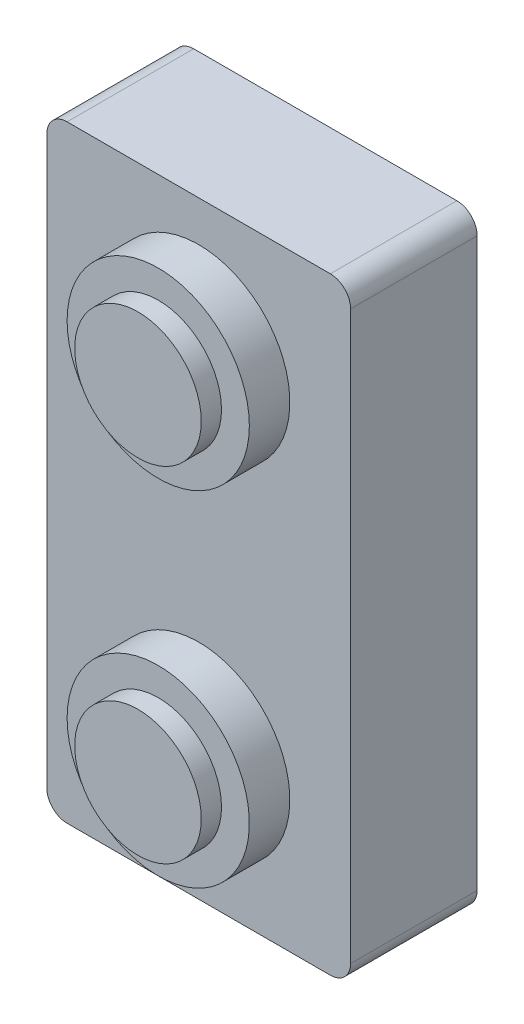
SolidWorks part; units mm, degrees
ref_plane "前视基准面" through (0, 0, 0) normal (0, 0, 1) x (1, 0, 0)
ref_plane "上视基准面" through (0, 0, 0) normal (0, 1, 0) x (1, 0, 0)
ref_plane "右视基准面" through (0, 0, 0) normal (1, 0, 0) x (0, 0, -1)
sketch "草图1" plane through (0, 0, 0) normal (0, 0, 1) x (1, 0, 0)
  line L0 (0, 0) -> (50000, 0) construction
  line L1 (0, 0) -> (0, -50000) construction
  line L3 (15, 30) -> (-15, 30)
  line L4 (15, 30) -> (15, -30)
  line L5 (15, -30) -> (-15, -30)
  line L6 (-15, 30) -> (-15, -30)
extrude "凸台-拉伸1" add sketch "草图1" along normal blind 12.5
sketch "草图2" plane through (0, 0, 12.5) normal (0, 0, 1) x (1, 0, 0)
  line L0 (0, 0) -> (0, 50000) construction
  line L1 (0, 0) -> (50000, 0) construction
  line L2 (-15, 30) -> (35340.3391, -35325.3391) construction
  line L3 (15, -30) -> (15, 30) construction
  line L4 (15, 30) -> (-35340.3391, -35325.3391) construction
  line L5 (-15, 30) -> (-15, -30) construction
  line L6 (-15, 0) -> (35340.3391, -35355.3391) construction
  line L7 (15, 0) -> (-35340.3391, -35355.3391) construction
  circle A2 centre (0, 17) radius 9
  circle A3 centre (0, -17) radius 9
  point P10 (15, 0)
  point P16 (-15, 0)
  dimension "D1" = 34
extrude "凸台-拉伸2" add sketch "草图2" along normal blind 4
sketch "草图3" plane through (0, 0, 16.5) normal (0, 0, 1) x (1, 0, 0)
  circle A0 centre (0, 17) radius 6.25
  circle A1 centre (0, -17) radius 6.25
extrude "凸台-拉伸3" add sketch "草图3" along normal blind 2
fillet "圆角1" radius 2 4 edges at (-15, 30, 6.25) (15, 30, 6.25) (-15, -30, 6.25) (15, -30, 6.25)
sketch "草图4" plane through (-15, 0, 0) normal (-1, 0, 0) x (0, 0, 1)
  line L0 (0, 28) -> (12.5, -28)
  line L1 (0, 0) -> (12.5, 0)
  line L2 (0, 28) -> (0, -28) construction
  line L3 (12.5, 28) -> (12.5, -28) construction
  circle A0 centre (6.25, 0) radius 4
extrude "切除-拉伸1" cut sketch "草图4" against normal blind 10 contours L0 A0 L1 | L1 A0 L0 | L0 A0 L1 | L1 A0 L0
